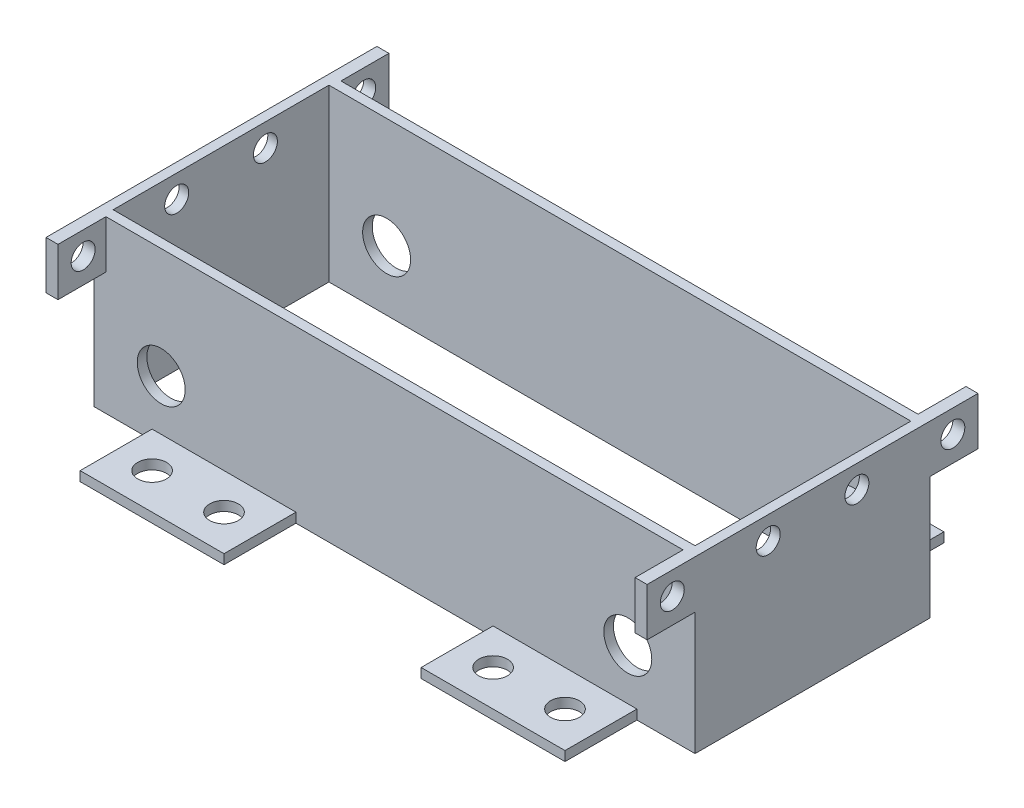
SolidWorks part; units mm, degrees
ref_plane "Front Plane" through (0, 0, 0) normal (0, 0, 1) x (1, 0, 0)
ref_plane "Top Plane" through (0, 0, 0) normal (0, 1, 0) x (1, 0, 0)
ref_plane "Right Plane" through (0, 0, 0) normal (1, 0, 0) x (0, 0, -1)
sketch "Sketch1" plane through (0, 0, 0) normal (0, 0, 1) x (1, 0, 0)
  line L0 (97.29, 0) -> (0, 0) construction
  line L1 (0, 0) -> (97.29, 0) construction
  line L2 (0, 8.025) -> (97.29, 8.025) construction
  line L3 (0, -8.025) -> (97.29, -8.025) construction
  line L4 (105.315, 0) -> (111.315, 0) construction
  line L5 (-14.025, -12.525) -> (111.315, -12.525)
  line L6 (-14.025, -12.525) -> (-14.025, 23.025)
  line L7 (-14.025, 23.025) -> (111.315, 23.025)
  line L9 (97.29, -8.025) -> (97.29, -12.525) construction
  line L10 (97.29, 8.025) -> (97.29, 23.025) construction
  line L11 (111.315, -12.525) -> (111.315, 23.025)
  circle A0 centre (0, 0) radius 8.025 construction
  circle A1 centre (97.29, 0) radius 8.025 construction
  arc A2 (0, 8.025) -> (0, -8.025) centre (0, 0) ccw construction
  arc A3 (97.29, -8.025) -> (97.29, 8.025) centre (97.29, 0) ccw construction
  circle A4 centre (0, 0) radius 5
  circle A5 centre (97.29, 0) radius 5
  point P5 (48.645, 0)
  point P18 (48.645, -12.525)
  dimension "D1" = 16.05
  dimension "D3" = 10
  dimension "D2" = 97.29
  dimension "D4" = 15
  dimension "D5" = 4.5
  dimension "D6" = 6
extrude "Boss-Extrude1" add sketch "Sketch1" along normal blind 2
sketch "Sketch2" plane through (0, 0, 0) normal (0, 0, -1) x (-1, 0, 0)
  line L0 (-111.315, 23.025) -> (14.025, 23.025) construction
  line L1 (-111.315, -12.525) -> (-109.315, -12.525)
  line L2 (-111.315, -12.525) -> (-111.315, 23.025)
  line L3 (-111.315, 23.025) -> (-109.315, 23.025)
  line L4 (-109.315, -12.525) -> (-109.315, 23.025)
  dimension "D1" = 2
extrude "Boss-Extrude2" add sketch "Sketch2" along normal blind 45
ref_plane "Plane1" through (48.645, 0, 0) normal (1, 0, 0) x (0, 0, -1)
mirror "Mirror1" about plane through (48.645, 0, 0) normal (1, 0, 0) of "Boss-Extrude2"
ref_plane "Plane2" through (0, 0, -22.5) normal (0, 0, -1) x (-1, 0, 0)
sketch "Sketch3" plane through (111.315, 0, 0) normal (1, 0, 0) x (0, 0, -1)
  line L0 (0, 23.025) -> (45, 23.025) construction
  line L1 (-2, 23.025) -> (45, 23.025) construction
  line L4 (0, 23.025) -> (13.25, 18.275) construction
  line L5 (22.5, 23.025) -> (22.5, -12.525) construction
  line L6 (-2, -12.525) -> (45, -12.525) construction
  circle A0 centre (13.25, 18.275) radius 2.5
  circle A2 centre (31.75, 18.275) radius 2.5
  circle A3 centre (-6.75, 18.275) radius 2.5
  circle A4 centre (51.75, 18.275) radius 2.5
  point P0 (0, 0)
  dimension "D2" = 5
  dimension "D1" = 4.75
  dimension "D3" = 2
  dimension "D5" = 20
  dimension "D6" = 9.25
  dimension "D4" = 2
sketch "Sketch4" plane through (0, 0, 2) normal (0, 0, 1) x (1, 0, 0)
  line L0 (48.645, 23.025) -> (48.645, -12.525) construction
  line L1 (-1.905, -12.525) -> (28.095, -12.525)
  line L2 (-1.905, -12.525) -> (-1.905, -10.525)
  line L3 (-1.905, -10.525) -> (28.095, -10.525)
  line L4 (28.095, -12.525) -> (28.095, -10.525)
  line L5 (111.315, 23.025) -> (-14.025, 23.025) construction
  line L6 (-14.025, -12.525) -> (111.315, -12.525) construction
  line L7 (13.095, -12.525) -> (48.645, 23.025) construction
  line L8 (99.195, -10.525) -> (69.195, -10.525)
  line L9 (69.195, -12.525) -> (69.195, -10.525)
  line L10 (99.195, -12.525) -> (69.195, -12.525)
  line L11 (99.195, -12.525) -> (99.195, -10.525)
  dimension "D1" = 45
  dimension "D2" = 30
  dimension "D3" = 2
extrude "Boss-Extrude3" add sketch "Sketch4" along normal blind 15
sketch "Sketch5" plane through (0, 0, 2) normal (0, 0, 1) x (1, 0, 0)
  line L0 (48.645, 23.025) -> (48.645, -12.525) construction
  line L1 (-14.025, 23.025) -> (-11.525, 23.025)
  line L2 (-14.025, 23.025) -> (-14.025, 13.025)
  line L3 (-14.025, 13.025) -> (-11.525, 13.025)
  line L4 (-11.525, 23.025) -> (-11.525, 13.025)
  line L5 (111.315, 23.025) -> (-14.025, 23.025) construction
  line L6 (28.095, -12.525) -> (69.195, -12.525) construction
  line L7 (111.315, 13.025) -> (108.815, 13.025)
  line L8 (108.815, 23.025) -> (108.815, 13.025)
  line L9 (111.315, 23.025) -> (108.815, 23.025)
  line L10 (111.315, 23.025) -> (111.315, 13.025)
  dimension "D1" = 2.5
  dimension "D2" = 10
extrude "Boss-Extrude4" add sketch "Sketch5" along normal blind 10
extrude "Cut-Extrude1" cut sketch "Sketch3" against normal through all
sketch "Sketch6" plane through (0, -10.525, 0) normal (0, 1, 0) x (1, 0, 0)
  line L0 (-1.905, -2) -> (13.095, -17) construction
  line L1 (28.095, -17) -> (-1.905, -17) construction
  line L2 (13.095, -17) -> (13.095, -2) construction
  line L3 (28.095, -2) -> (-1.905, -2) construction
  line L4 (48.645, -2) -> (48.645, -17) construction
  line L5 (108.815, -2) -> (-11.525, -2) construction
  line L6 (48.645, -17) -> (28.095, -17) construction
  circle A0 centre (5.595, -9.5) radius 3
  circle A1 centre (20.595, -9.5) radius 3
  circle A2 centre (91.695, -9.5) radius 3
  circle A3 centre (76.695, -9.5) radius 3
  dimension "D1" = 6
extrude "Cut-Extrude2" cut sketch "Sketch6" against normal through all
mirror "Mirror2" about plane through (0, 0, -22.5) normal (0, 0, -1) of "Cut-Extrude2", "Cut-Extrude1", "Boss-Extrude4", "Boss-Extrude3", "Boss-Extrude1"
